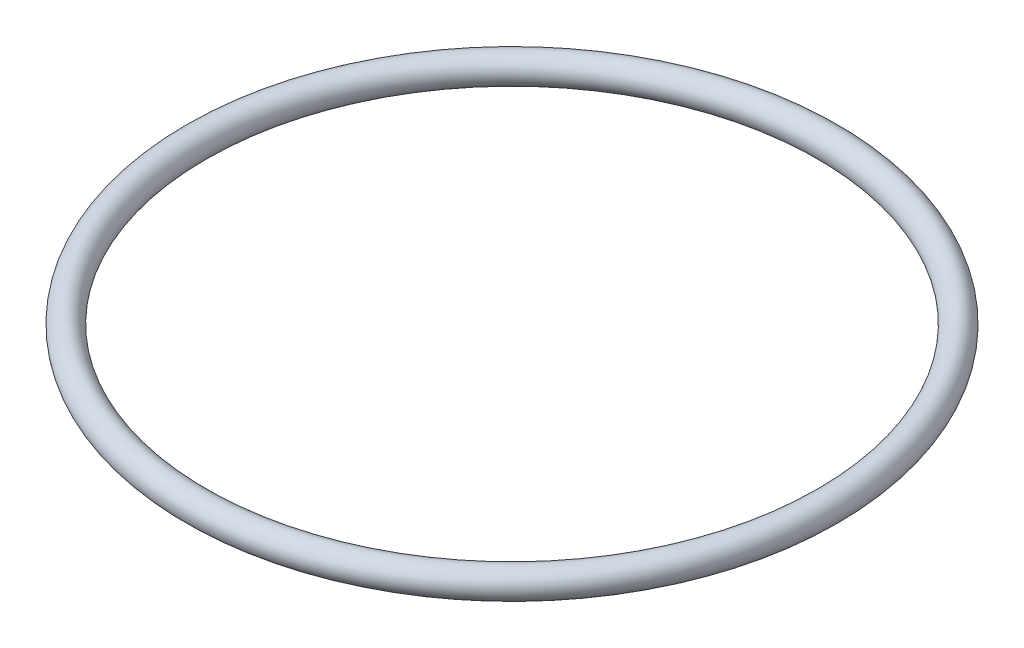
SolidWorks part; units mm, degrees
material "NEOPRENE"
ref_plane "Front Plane" through (0, 0, 0) normal (0, 0, 1) x (1, 0, 0)
ref_plane "Top Plane" through (0, 0, 0) normal (0, 1, 0) x (1, 0, 0)
ref_plane "Right Plane" through (0, 0, 0) normal (1, 0, 0) x (0, 0, -1)
sketch "Sketch1" plane through (0, 0, 0) normal (0, 1, 0) x (1, 0, 0)
  circle A0 centre (0, 0) radius 70.4478 construction
  circle A1 centre (0, 0) radius 64.4478 construction
  circle A2 centre (0, 0) radius 67.4478
  dimension "D2" = 128.8957
  dimension "D1" = 6
  dimension "D3" = 3
sketch "Sketch2" plane through (0, 0, 0) normal (0, 0, 1) x (1, 0, 0)
  line L1 (67.4478, 0) -> (-67.4478, 0) construction
  circle A0 centre (-67.4478, 0) radius 3
  dimension "D1" = 6
  dimension "D2" = 67.4478
sweep "Sweep1" add profiles "Sketch2" path "Sketch1"
equation "\"FuelDia\"= 1.6524"
equation "\"OxDia\"= 1.82924"
equation "\"DistOrifice\"= 10"
equation "\"CantAngle\"= 25deg"
equation "\"RadialDistOrifice\"= 60"
equation "\"Chan_amt\"= 35"
equation "\"Chan_wid\"= 3"
equation "\"Chan_heig\"= 5"
equation "\"bolt_diam\"= 15"
equation "\"oring_inner\"= 128.8956920"
equation "\"oring_outer\"=143.374"
equation "\"oring_thickness\"=6"
equation "\"D1@Sketch1\"=\"oring_thickness\""
equation "\"D2@Sketch1\"=\"oring_inner\""
equation "\"D3@Sketch1\"=\"oring_thickness\"/2"
equation "\"D1@Sketch2\"=\"oring_thickness\""
equation "\"D2@Sketch2\"=(\"oring_inner\"/2)+(\"oring_thickness\"/2)"
equation "\"t_plate\"=15"
